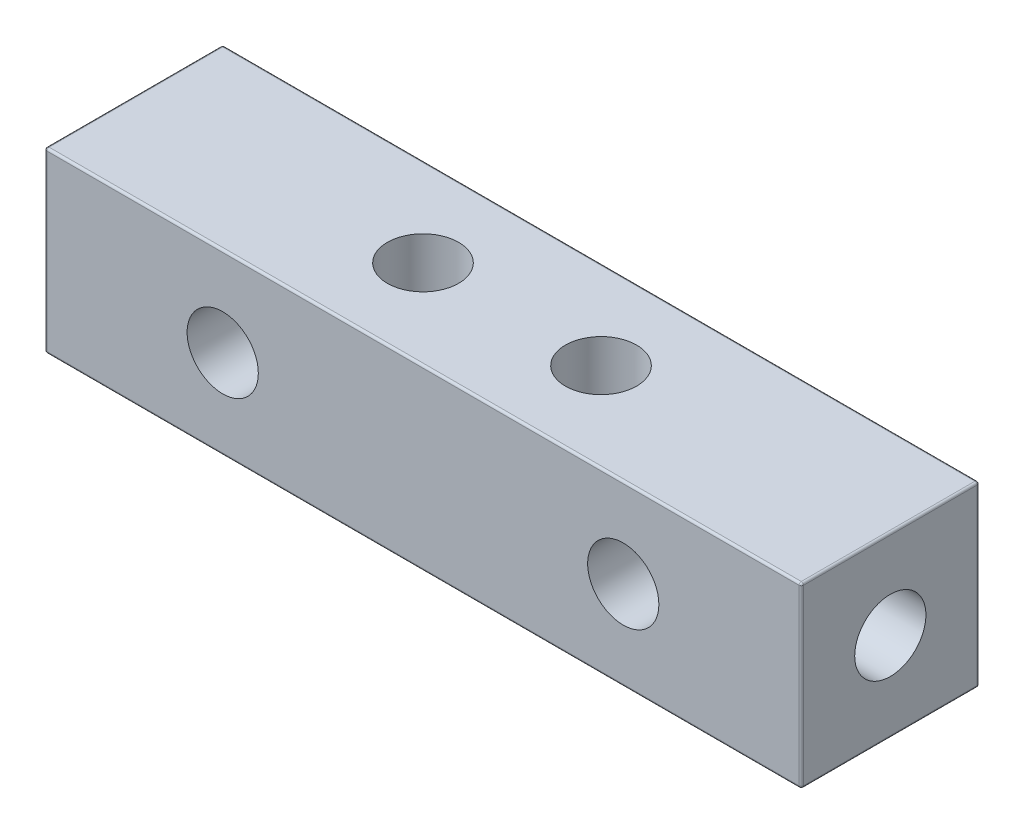
SolidWorks part; units mm, degrees
ref_plane "前视基准面" through (0, 0, 0) normal (0, 0, 1) x (1, 0, 0)
ref_plane "上视基准面" through (0, 0, 0) normal (0, 1, 0) x (1, 0, 0)
ref_plane "右视基准面" through (0, 0, 0) normal (1, 0, 0) x (0, 0, -1)
other "Configuration Table"
sketch "草图1" plane through (0, 0, 0) normal (1, 0, 0) x (0, 0, -1)
  line L1 (-4, 4) -> (4, 4)
  line L2 (-4, 4) -> (-4, -4)
  line L3 (-4, -4) -> (4, -4)
  line L4 (4, 4) -> (4, -4)
  line L5 (-4, 4) -> (4, -4) construction
  line L6 (-4, -4) -> (4, 4) construction
  point P0 (0, 0)
  point P6 (4, 0.034)
  dimension "D1" = 8
extrude "凸台-拉伸1" add sketch "草图1" along normal blind 34
fillet "圆角1" radius 0.1 12 edges at (17, -4, 4) (0, 0, 4) (17, -4, -4) (0, 0, -4) (17, 4, -4) (17, 4, 4) (0, 4, 0) (34, -4, 0) (34, 0, 4) (34, 4, 0) (34, 0, -4) (0, -4, 0)
sketch "草图2" plane through (0, 0, 0) normal (-1, 0, 0) x (0, 0, 1)
  circle A0 centre (0, 0) radius 1.6
  dimension "D1" = 3.2
extrude "切除-拉伸1" cut sketch "草图2" against normal through all
sketch "草图3" plane through (0, 0, 4) normal (0, 0, 1) x (1, 0, 0)
  line L0 (0, 0) -> (8, 0) construction
  line L1 (8, 0) -> (26, 0) construction
  circle A0 centre (8, 0) radius 1.6
  circle A1 centre (26, 0) radius 1.6
  dimension "D3" = 3.2
  dimension "D4" = 3.2
  dimension "D1" = 8
  dimension "D2" = 18
extrude "切除-拉伸2" cut sketch "草图3" against normal through all
sketch "草图4" plane through (0, 4, 0) normal (0, 1, 0) x (1, 0, 0)
  line L0 (34, 0) -> (21, 0) construction
  line L1 (34, 4) -> (34, -4) construction
  line L2 (21, 0) -> (13, 0) construction
  circle A0 centre (21, 0) radius 1.6
  circle A1 centre (13, 0) radius 1.6
  dimension "D3" = 3.2
  dimension "D4" = 3.2
  dimension "D1" = 13
  dimension "D2" = 8
extrude "切除-拉伸3" cut sketch "草图4" against normal through all
